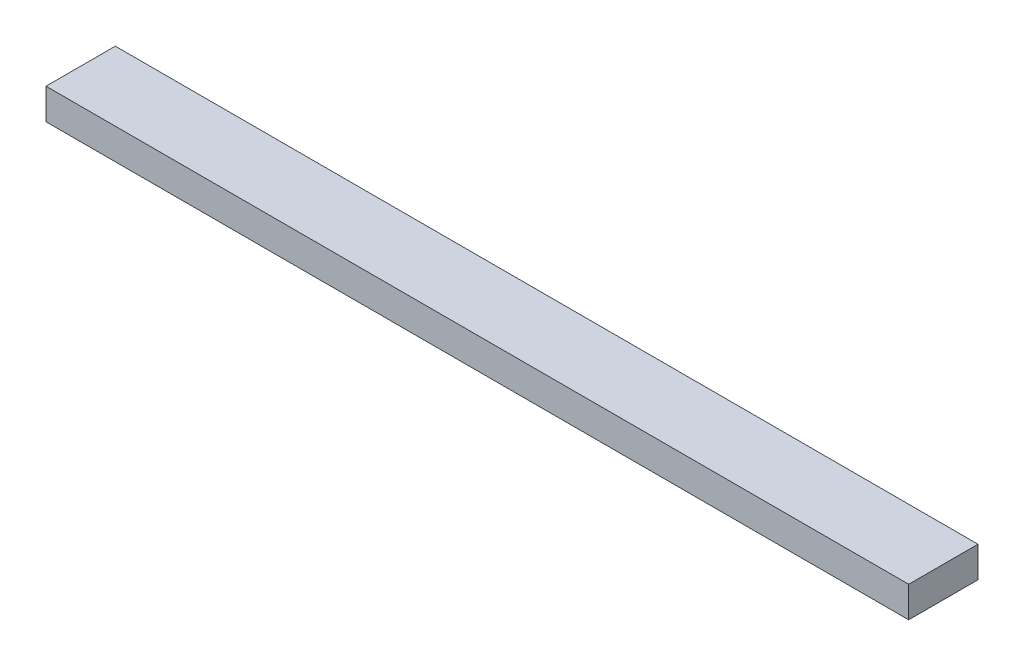
SolidWorks part; units mm, degrees
material "Silicon"
ref_plane "Front Plane" through (0, 0, 0) normal (0, 0, 1) x (1, 0, 0)
ref_plane "Top Plane" through (0, 0, 0) normal (0, 1, 0) x (1, 0, 0)
ref_plane "Right Plane" through (0, 0, 0) normal (1, 0, 0) x (0, 0, -1)
sketch "Sketch1" plane through (0, 0, 0) normal (0, 1, 0) x (1, 0, 0)
  line L1 (-45.5408, 30.6089) -> (96.6992, 30.6089)
  line L2 (-45.5408, 30.6089) -> (-45.5408, 19.1789)
  line L3 (-45.5408, 19.1789) -> (96.6992, 19.1789)
  line L4 (96.6992, 30.6089) -> (96.6992, 19.1789)
  dimension "D1" = 142.24
  dimension "D2" = 11.43
extrude "Boss-Extrude1" add sketch "Sketch1" along normal blind 5.08
